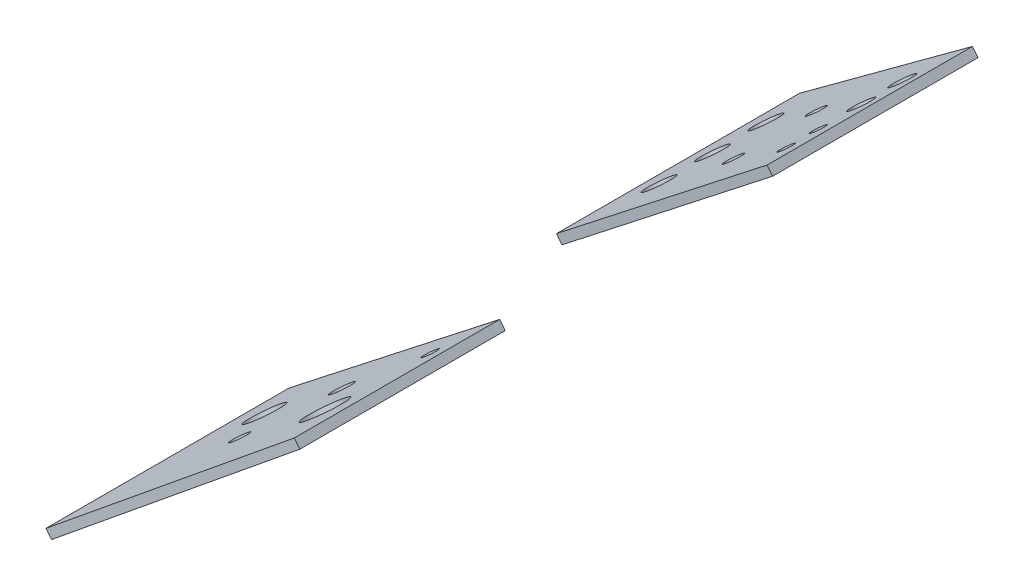
SolidWorks part; units mm, degrees
ref_plane "Front Plane" through (0, 0, 0) normal (0, 0, 1) x (1, 0, 0)
ref_plane "Top Plane" through (0, 0, 0) normal (0, 1, 0) x (1, 0, 0)
ref_plane "Right Plane" through (0, 0, 0) normal (1, 0, 0) x (0, 0, -1)
sketch3d "3DSketch1"
  line L4 (773.7071, 679.8403, 129.8406) -> (773.7071, 679.5817, 0) construction
  line L5 (773.7071, 679.5817, 0) -> (773.7071, 679.8403, -129.8406) construction
  line L6 (394.3882, 355.8329, 258.042) -> (773.7071, 652.4915, 190.2318) construction
  line L7 (394.3882, 355.8329, -258.042) -> (773.7071, 652.4915, -190.2318) construction
  arc A2 (773.7071, 599.8405, 210) -> (773.7071, 679.8403, 129.8406) centre (773.7071, 599.8405, 130) ccw construction
  arc A3 (773.7071, 679.8403, -129.8406) -> (773.7071, 599.8405, -210) centre (773.7071, 599.8405, -130) ccw construction
  point P4 (693.7071, 599.8405, 130)
  point P6 (693.7071, 599.8405, -130)
ref_plane "Plane1" through (-22.9962, 29.4039, 0) normal (0.6161, -0.7877, 0) x (-0.7877, -0.6161, 0)
sketch "Sketch2" plane through (-22.9962, 29.4039, 0) normal (0.6161, -0.7877, 0) x (-0.7877, -0.6161, 0)
  line L0 (-1011.422, 190.2318) -> (-1011.422, -190.2318)
  line L1 (-1011.422, -190.2318) -> (-861.422, -211.3543)
  line L2 (-529.8732, -258.042) -> (-1011.422, -190.2318) construction
  line L3 (-861.422, -211.3543) -> (-861.422, 211.3543)
  line L4 (-529.8732, 258.042) -> (-1011.422, 190.2318) construction
  line L5 (-861.422, 211.3543) -> (-1011.422, 190.2318)
  dimension "D1" = 150
extrude "Boss-Extrude1" add sketch "Sketch2" against normal mid plane 5 from offset 7.95 offset against normal yes
sketch "Sketch3" plane through (-29.434, 37.6354, 0) normal (-0.6161, 0.7877, 0) x (0.7877, 0.6161, 0)
  line L0 (1011.422, 190.2318) -> (1011.422, -190.2318) construction
  line L1 (1011.422, 75) -> (861.422, 75)
  line L2 (1011.422, 75) -> (1011.422, -75)
  line L3 (1011.422, -75) -> (861.422, -75)
  line L4 (861.422, 75) -> (861.422, -75)
  line L5 (861.422, -211.3543) -> (861.422, 211.3543) construction
  line L6 (1011.422, 0) -> (865.1672, 0) construction
  dimension "D1" = 150
extrude "Cut-Extrude2" cut sketch "Sketch3" along normal mid plane 15
sketch "Sketch4" plane through (-29.434, 37.6354, 0) normal (-0.6161, 0.7877, 0) x (0.7877, 0.6161, 0)
  line L0 (993.418, 165.0363) -> (993.418, 142.0363) construction
  line L1 (1011.422, 190.2318) -> (1011.422, 75) construction
  circle A0 centre (993.418, 165.0363) radius 6.5
  circle A1 centre (993.418, 142.0363) radius 6.5
  circle A2 centre (993.418, 165.0363) radius 9.75 construction
  circle A3 centre (993.418, 142.0363) radius 9.75 construction
  dimension "D1" = 13
  dimension "D2" = 19.5
  dimension "D3" = 19.5
  dimension "D4" = 23
extrude "Cut-Extrude3" cut sketch "Sketch4" against normal blind 10
sketch "Sketch5" plane through (-29.434, 37.6354, 0) normal (-0.6161, 0.7877, 0) x (0.7877, 0.6161, 0)
  line L0 (993.418, 117.8424) -> (993.418, 99.8424) construction
  line L1 (993.418, 142.0363) -> (993.418, 117.8424) construction
  circle A0 centre (993.418, 117.8424) radius 4.1
  circle A1 centre (993.418, 117.8424) radius 4.5 construction
  circle A2 centre (993.418, 99.8424) radius 4.1
  circle A3 centre (993.418, 99.8424) radius 4.5 construction
  dimension "D1" = 8.2
  dimension "D2" = 9
  dimension "D3" = 18
extrude "Cut-Extrude4" cut sketch "Sketch5" against normal blind 10
sketch "Sketch6" plane through (-29.434, 37.6354, 0) normal (-0.6161, 0.7877, 0) x (0.7877, 0.6161, 0)
  circle A0 centre (938.5219, 159.9014) radius 5
  circle A1 centre (938.5219, 159.9014) radius 14.4 construction
  circle A2 centre (938.5219, 113.5014) radius 5
  circle A3 centre (938.5219, 113.5014) radius 14.4 construction
  dimension "D1" = 28.8
  dimension "D2" = 10
  dimension "D3" = 32
extrude "Cut-Extrude5" cut sketch "Sketch6" against normal blind 10
sketch "Sketch7" plane through (-29.434, 37.6354, 0) normal (-0.6161, 0.7877, 0) x (0.7877, 0.6161, 0)
  circle A0 centre (887.5743, 171.9385) radius 8
  circle A1 centre (887.5743, 141.9385) radius 8
  circle A2 centre (887.5743, 111.9385) radius 8
  circle A3 centre (887.5743, 171.9385) radius 10.75 construction
  dimension "D1" = 16
  dimension "D2" = 21.5
  dimension "D3" = 30
  dimension "D4" = 30
extrude "Cut-Extrude6" cut sketch "Sketch7" against normal blind 10
sketch "Sketch8" plane through (-29.434, 37.6354, 0) normal (-0.6161, 0.7877, 0) x (0.7877, 0.6161, 0)
  line L1 (993.418, 99.8424) -> (993.418, -99.8424) construction
  line L2 (993.418, 0) -> (754.5119, 0) construction
  circle A0 centre (993.418, -99.8424) radius 4.1
  circle A1 centre (993.418, 99.8424) radius 4.1 construction
  circle A2 centre (981.0583, -149.1489) radius 11.5
  circle A3 centre (981.0583, -149.1489) radius 17 construction
  circle A4 centre (920.3291, -149.1489) radius 5
  dimension "D1" = 34
  dimension "D2" = 23
  dimension "D3" = 10
extrude "Cut-Extrude7" cut sketch "Sketch8" against normal blind 10
sketch "Sketch9" plane through (-29.434, 37.6354, 0) normal (-0.6161, 0.7877, 0) x (0.7877, 0.6161, 0)
  circle A0 centre (893.323, -113.9235) radius 10
  dimension "D1" = 20
extrude "Cut-Extrude8" cut sketch "Sketch9" against normal blind 10
sketch "Sketch10" plane through (-29.434, 37.6354, 0) normal (-0.6161, 0.7877, 0) x (0.7877, 0.6161, 0)
  line L0 (948.323, -113.9235) -> (893.323, -113.9235) construction
  circle A0 centre (948.323, -113.9235) radius 6
  dimension "D1" = 12
  dimension "D2" = 55
extrude "Cut-Extrude9" cut sketch "Sketch10" against normal blind 10
